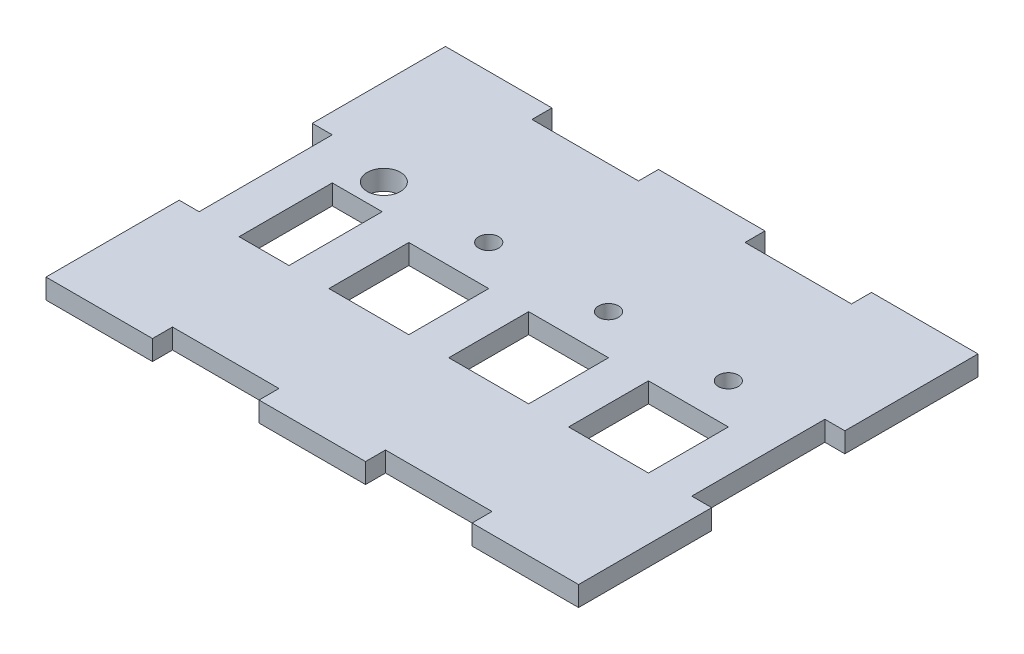
SolidWorks part; units mm, degrees
ref_plane "Front Plane" through (0, 0, 0) normal (0, 0, 1) x (1, 0, 0)
ref_plane "Top Plane" through (0, 0, 0) normal (0, 1, 0) x (1, 0, 0)
ref_plane "Right Plane" through (0, 0, 0) normal (1, 0, 0) x (0, 0, -1)
sketch "Top and Bottom" plane through (0, 0, 0) normal (0, 1, 0) x (1, 0, 0)
  line L0 (32, 60) -> (48, 60)
  line L1 (0, 0) -> (16, 0)
  line L2 (0, 0) -> (0, 20)
  line L3 (0, 60) -> (16, 60)
  line L4 (80, 0) -> (80, 20)
  line L5 (64, 60) -> (80, 60)
  line L6 (16, 60) -> (16, 57)
  line L7 (16, 57) -> (32, 57)
  line L8 (32, 60) -> (32, 57)
  line L9 (40.75, 31.75) -> (52.75, 31.75)
  line L10 (48, 60) -> (48, 57)
  line L11 (48, 57) -> (64, 57)
  line L12 (64, 60) -> (64, 57)
  line L13 (22.75, 31.75) -> (34.75, 31.75)
  line L14 (64, 0) -> (64, 3)
  line L15 (48, 3) -> (64, 3)
  line L16 (48, 0) -> (48, 3)
  line L17 (32, 0) -> (32, 3)
  line L18 (16, 0) -> (16, 3)
  line L19 (16, 3) -> (32, 3)
  line L20 (64, 0) -> (80, 0)
  line L21 (32, 0) -> (48, 0)
  line L22 (0, 40) -> (0, 60)
  line L23 (0, 40) -> (3, 40)
  line L24 (80, 40) -> (77, 40)
  line L25 (0, 20) -> (3, 20)
  line L26 (3, 40) -> (3, 20)
  line L27 (77, 40) -> (77, 20)
  line L28 (80, 20) -> (77, 20)
  line L29 (80, 40) -> (80, 60)
  line L30 (22.75, 31.75) -> (22.75, 19.75)
  line L31 (22.75, 19.75) -> (34.75, 19.75)
  line L32 (34.75, 31.75) -> (34.75, 19.75)
  line L33 (40.75, 31.75) -> (40.75, 19.75)
  line L34 (40.75, 19.75) -> (52.75, 19.75)
  line L35 (52.75, 31.75) -> (52.75, 19.75)
  line L36 (58.75, 31.75) -> (70.75, 31.75)
  line L37 (58.75, 31.75) -> (58.75, 19.75)
  line L38 (58.75, 19.75) -> (70.75, 19.75)
  line L39 (70.75, 31.75) -> (70.75, 19.75)
  line L41 (9.25, 33.75) -> (16.75, 33.75)
  line L42 (9.25, 33.75) -> (9.25, 19.75)
  line L43 (9.25, 19.75) -> (16.75, 19.75)
  line L44 (16.75, 33.75) -> (16.75, 19.75)
  circle A0 centre (28.75, 37.75) radius 1.5
  circle A1 centre (46.75, 37.75) radius 1.5
  circle A2 centre (64.75, 37.75) radius 1.5
  circle A3 centre (13, 37.75) radius 2.5
  dimension "D16" = 3
  dimension "D18" = 6
  dimension "D20" = 3
  dimension "D21" = 3
  dimension "D22" = 6
  dimension "D28" = 5
  dimension "D29" = 4
  dimension "D1" = 60
  dimension "D2" = 80
  dimension "D3" = 3
  dimension "D4" = 16
  dimension "D5" = 16
  dimension "D6" = 16
  dimension "D7" = 3
  dimension "D8" = 16
  dimension "D9" = 12
  dimension "D10" = 3
  dimension "D11" = 20
  dimension "D12" = 20
  dimension "D13" = 12
  dimension "D14" = 6
  dimension "D15" = 6
  dimension "D17" = 6
  dimension "D19" = 6
  dimension "D23" = 6
  dimension "D24" = 6
  dimension "D25" = 7.5
  dimension "D26" = 14
  dimension "D27" = 0
  dimension "D30" = 6
  dimension "D31" = 9.25
  dimension "D32" = 3.75
  dimension "D33" = 19.75
  dimension "D34" = 12
  dimension "D35" = 12
  dimension "D36" = 12
  dimension "D37" = 12
  dimension "D38" = 0
  dimension "D39" = 0
  dimension "D40" = 20
  dimension "D41" = 20
extrude "Top and Bottom Extruded" add sketch "Top and Bottom" along normal blind 3
